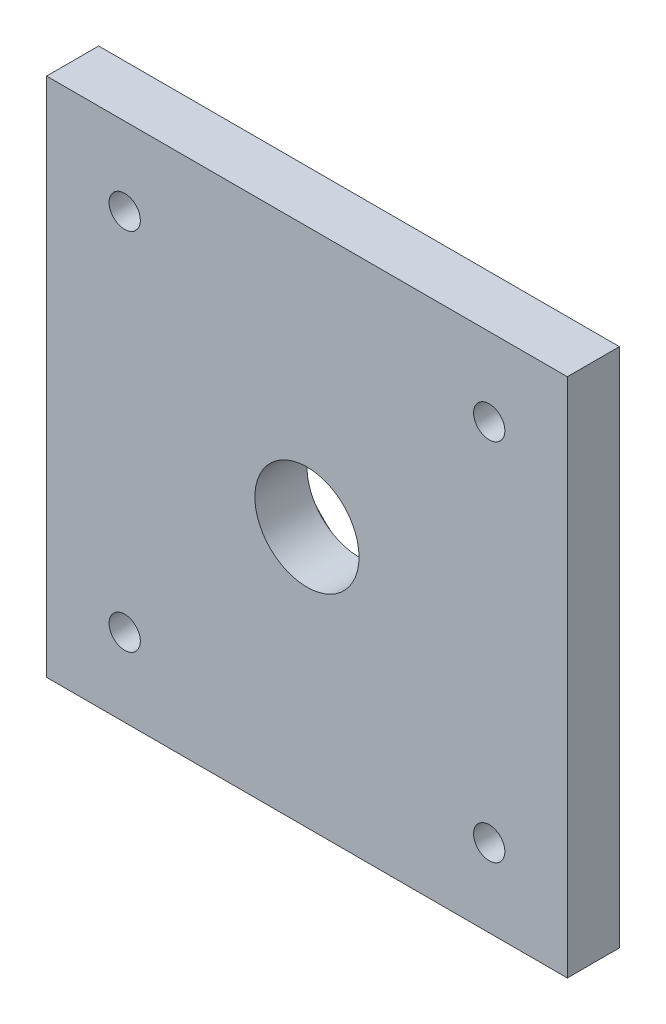
SolidWorks part; units mm, degrees
ref_plane "Front Plane" through (0, 0, 0) normal (0, 0, 1) x (1, 0, 0)
ref_plane "Top Plane" through (0, 0, 0) normal (0, 1, 0) x (1, 0, 0)
ref_plane "Right Plane" through (0, 0, 0) normal (1, 0, 0) x (0, 0, -1)
sketch "Sketch1" plane through (0, 0, 0) normal (0, 0, 1) x (1, 0, 0)
  circle A0 centre (0, 0) radius 12 construction
  circle A1 centre (0, 0) radius 12
  circle A4 centre (0, 0) radius 17
  dimension "D1" = 5
extrude "Boss-Extrude1" add sketch "Sketch1" against normal blind 5
sketch "Sketch2" plane through (0, 0, 0) normal (0, 0, 1) x (1, 0, 0)
  line L1 (-25, 25) -> (25, 25)
  line L2 (-25, 25) -> (-25, -25)
  line L3 (-25, -25) -> (25, -25)
  line L4 (25, 25) -> (25, -25)
  dimension "D1" = 50
  dimension "D2" = 50
  dimension "D3" = 25
  dimension "D4" = 25
extrude "Boss-Extrude2" add sketch "Sketch2" along normal blind 5
sketch "Sketch3" plane through (0, 0, 5) normal (0, 0, 1) x (1, 0, 0)
  circle A0 centre (0, 0) radius 5
extrude "Cut-Extrude1" cut sketch "Sketch3" against normal through all
sketch "Sketch4" plane through (0, 0, 5) normal (0, 0, 1) x (1, 0, 0)
  line L0 (0, 25) -> (0, -25) construction
  line L1 (25, 25) -> (-25, 25) construction
  line L2 (-25, -25) -> (25, -25) construction
  line L3 (0, -25) -> (-25, 0) construction
  line L4 (-25, 25) -> (-25, -25) construction
  line L5 (-25, 0) -> (25, 0) construction
  line L6 (25, -25) -> (25, 25) construction
  circle A0 centre (-17.5, 17.5) radius 1.5
  circle A2 centre (17.5, 17.5) radius 1.5
  circle A3 centre (-17.5, -17.5) radius 1.5
  circle A4 centre (17.5, -17.5) radius 1.5
  dimension "D1" = 3
  dimension "D2" = 17.5
  dimension "D3" = 17.5
extrude "Cut-Extrude2" cut sketch "Sketch4" against normal through all
